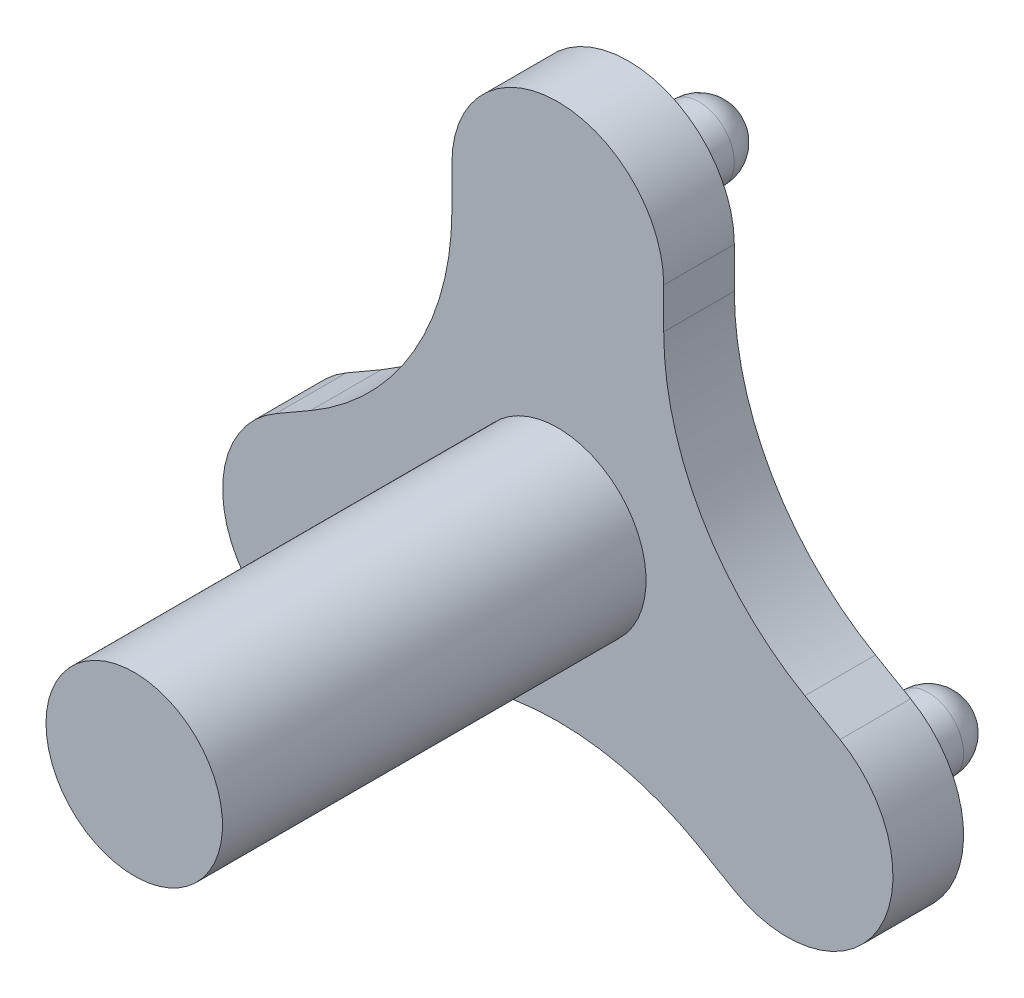
SolidWorks part; units mm, degrees
ref_plane "Front Plane" through (0, 0, 0) normal (0, 0, 1) x (1, 0, 0)
ref_plane "Top Plane" through (0, 0, 0) normal (0, 1, 0) x (1, 0, 0)
ref_plane "Right Plane" through (0, 0, 0) normal (1, 0, 0) x (0, 0, -1)
sketch "Sketch2" plane through (0, 0, 0) normal (0, 0, 1) x (1, 0, 0)
  line L0 (0, 0) -> (0, 23.8125)
  line L1 (0, 0) -> (20.6222, -11.9063)
  line L2 (0, 0) -> (-20.6222, -11.9062)
  line L3 (9.525, 0) -> (9.525, 23.8125)
  line L4 (-4.7625, 8.2489) -> (-25.3847, -3.6574)
  line L5 (-4.7625, -8.2489) -> (15.8597, -20.1551)
  line L6 (-9.525, 0) -> (-9.525, 23.8125)
  line L7 (4.7625, -8.2489) -> (-15.8597, -20.1551)
  line L8 (4.7625, 8.2489) -> (25.3847, -3.6574)
  arc A0 (9.525, 0) -> (-9.525, 0) centre (0, 0) cw
  arc A1 (9.525, 23.8125) -> (-9.525, 23.8125) centre (0, 23.8125) ccw
  arc A2 (-4.7625, 8.2489) -> (4.7625, -8.2489) centre (0, 0) cw
  arc A3 (-25.3847, -3.6574) -> (-15.8597, -20.1551) centre (-20.6222, -11.9062) ccw
  arc A4 (-4.7625, -8.2489) -> (4.7625, 8.2489) centre (0, 0) cw
  arc A5 (15.8597, -20.1551) -> (25.3847, -3.6574) centre (20.6222, -11.9063) ccw
  point P7 (0, 0)
  dimension "D1" = 23.8125
  dimension "D3" = 9.525
  dimension "D4" = 9.525
  dimension "D2" = 3
extrude "Boss-Extrude1" add sketch "Sketch2" along normal blind 6.35
fillet "Fillet1" radius 25.4 3 edges at (9.525, 5.4993, 3.175) (0, -10.9985, 3.175) (-9.525, 5.4993, 3.175)
sketch "Sketch3" plane through (0, 0, 0) normal (0, 0, -1) x (-1, 0, 0)
  circle A0 centre (0, 23.8125) radius 3.175
  circle A1 centre (20.6222, -11.9062) radius 3.175
  circle A2 centre (-20.6222, -11.9063) radius 3.175
  point P4 (0, 0)
  point P9 (0, 0)
  dimension "D1" = 6.35
  dimension "D2" = 3
extrude "Boss-Extrude2" add sketch "Sketch3" along normal blind 9.525
fillet "Fillet2" radius 3.175 3 edges at (-23.7972, -11.9062, -9.525) (-3.175, 23.8125, -9.525) (17.4472, -11.9063, -9.525)
sketch "Sketch4" plane through (0, 0, 6.35) normal (0, 0, 1) x (1, 0, 0)
  circle A0 centre (0, 0) radius 7.9375
  dimension "D1" = 15.875
extrude "Boss-Extrude3" add sketch "Sketch4" along normal blind 38.1
